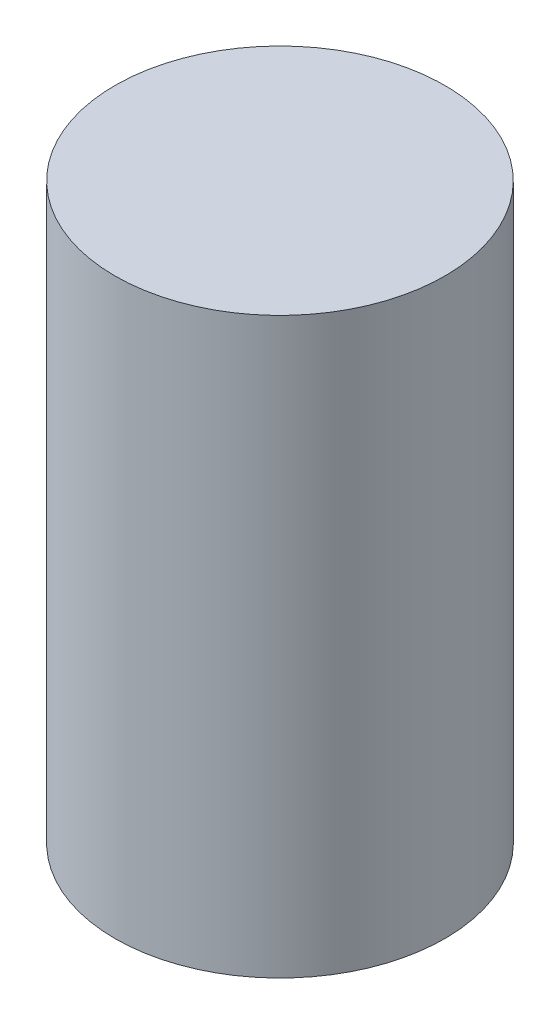
SolidWorks part; units mm, degrees
ref_plane "Front Plane" through (0, 0, 0) normal (0, 0, 1) x (1, 0, 0)
ref_plane "Top Plane" through (0, 0, 0) normal (0, 1, 0) x (1, 0, 0)
ref_plane "Right Plane" through (0, 0, 0) normal (1, 0, 0) x (0, 0, -1)
sketch "Sketch2" plane through (0, 0, 0) normal (0, 1, 0) x (1, 0, 0)
  circle A0 centre (0, 0) radius 6.9
  dimension "D1" = 13.8
extrude "Boss-Extrude1" add sketch "Sketch2" along normal blind 24
